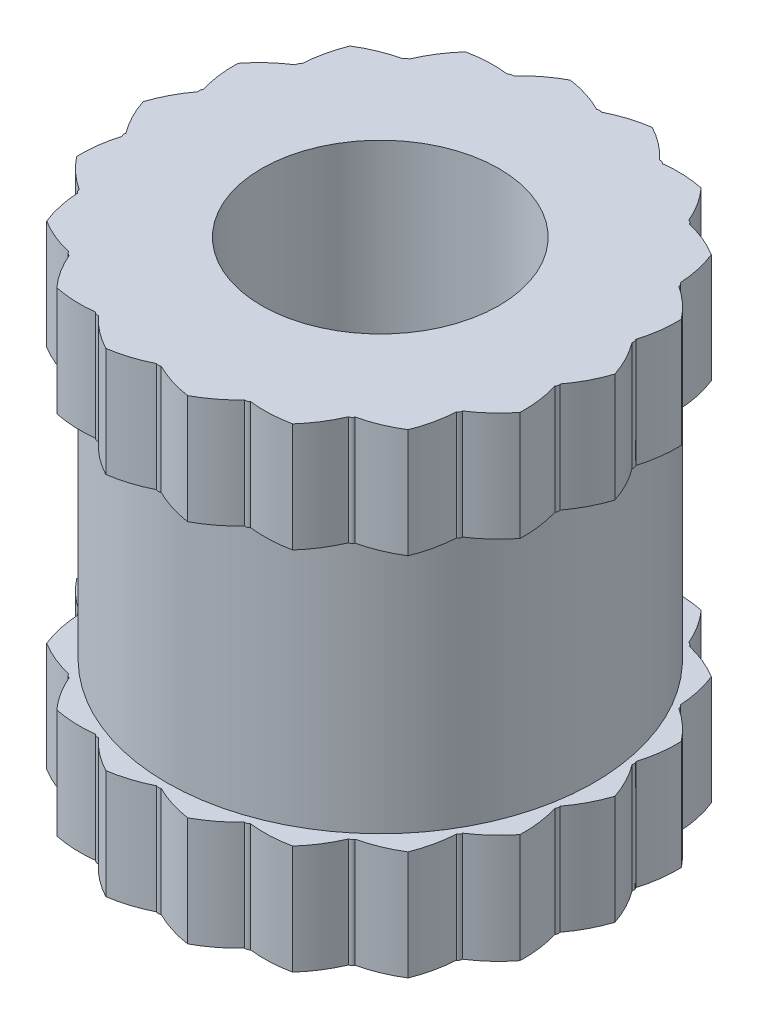
SolidWorks part; units mm, degrees
material "Pure Gold"
ref_plane "Front Plane" through (0, 0, 0) normal (0, 0, 1) x (1, 0, 0)
ref_plane "Top Plane" through (0, 0, 0) normal (0, 1, 0) x (1, 0, 0)
ref_plane "Right Plane" through (0, 0, 0) normal (1, 0, 0) x (0, 0, -1)
sketch "Sketch1" plane through (0, 0, 0) normal (0, 1, 0) x (1, 0, 0)
  circle A0 centre (0, 0) radius 2.51
  dimension "D1" = 5.02
extrude "Boss-Extrude1" add sketch "Sketch1" along normal blind 5
sketch "Sketch2" plane through (0, 5, 0) normal (0, 1, 0) x (1, 0, 0)
  line L0 (0, 1.885) -> (0, 2.4241) construction
  circle A15 centre (0, 0) radius 2.51 construction
  arc A20 (-0.5691, 2.4446) -> (0.0499, 2.2631) centre (-0.6172, 1.1347) cw
  arc A22 (-0.0499, 2.2631) -> (0.0336, 2.2232) centre (0, 2.2602) cw
  arc A23 (0.0499, 2.2631) -> (-0.0336, 2.2232) centre (0, 2.2602) ccw
  arc A24 (0.0336, 2.2232) -> (-0.0336, 2.2232) centre (0, 0) ccw
  arc A28 (0.5691, 2.4446) -> (-0.0499, 2.2631) centre (0.6172, 1.1347) ccw
  arc A29 (-0.5691, 2.4446) -> (0.5691, 2.4446) centre (0, 1.5831) cw
  point P17 (-0.4038, 2.4773)
  dimension "D3" = 0.05
extrude "Cut-Extrude2" cut sketch "Sketch2" against normal blind 5
pattern_circular "CirPattern1" count 18 every 20 about axis through (0, 0, 0.0136) along (0, 1, 0) of "Cut-Extrude2"
hole_wizard "M3 Tapped Hole1" positions "Sketch3" profile "Sketch5" tap size "M3" standard "ISO" end condition up to next
sketch "Sketch3" plane through (0, 5, 0) normal (0, 1, 0) x (1, 0, 0)
  point P0 (0, 0)
sketch "Sketch5" plane through (0, 5, 0) normal (1, 0, 0) x (0, 0, 1)
  line L0 (0, 0) -> (0, 5)
  line L1 (0, 5) -> (1.25, 5)
  line L2 (1.25, 5) -> (1.25, 0)
  line L5 (1.25, 0) -> (0, 0)
  line L11 (0, -6.35) -> (0, 107.95) construction
  dimension "Thread Major Dia." = 2.5
  dimension "Thru Tap Drill Depth" = 5
ref_plane "Plane2" through (0, 3.85, 0) normal (0, 1, 0) x (1, 0, 0)
sketch "Sketch8" plane through (0, 3.85, 0) normal (0, 1, 0) x (1, 0, 0)
  circle A0 centre (0, 0) radius 2.25
  circle A1 centre (0, 0) radius 3.25
  dimension "D1" = 4.5
  dimension "D2" = 1
extrude "Cut-Extrude3" cut sketch "Sketch8" against normal blind 2.7
